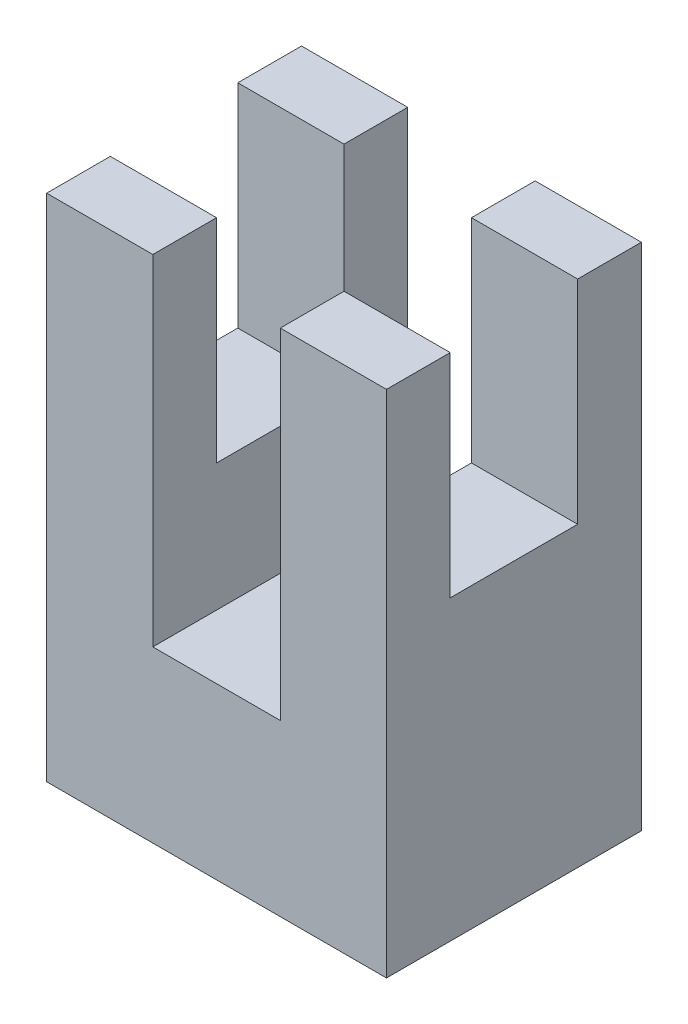
SolidWorks part; units mm, degrees
ref_plane "Alzado" through (0, 0, 0) normal (0, 0, 1) x (1, 0, 0)
ref_plane "Planta" through (0, 0, 0) normal (0, 1, 0) x (1, 0, 0)
ref_plane "Vista lateral" through (0, 0, 0) normal (1, 0, 0) x (0, 0, -1)
sketch "Croquis1" plane through (0, 0, 0) normal (0, 0, 1) x (1, 0, 0)
  line L0 (-20, 0) -> (20, 0)
  line L1 (20, 0) -> (20, 60)
  line L2 (20, 60) -> (7.5, 60)
  line L3 (7.5, 60) -> (7.5, 20)
  line L4 (7.5, 20) -> (-7.5, 20)
  line L5 (-7.5, 20) -> (-7.5, 60)
  line L6 (-7.5, 60) -> (-20, 60)
  line L7 (-20, 60) -> (-20, 0)
  point P11 (0, 0)
  dimension "D1" = 15
  dimension "D2" = 40
  dimension "D3" = 60
  dimension "D4" = 40
extrude "Saliente-Extruir1" add sketch "Croquis1" along normal mid plane 30
sketch "Croquis2" plane through (20, 0, 0) normal (1, 0, 0) x (0, 0, -1)
  line L0 (-7.5, 60) -> (-7.5, 35)
  line L1 (-15, 60) -> (15, 60) construction
  line L2 (-7.5, 35) -> (7.5, 35)
  line L3 (7.5, 35) -> (7.5, 60)
  line L4 (7.5, 60) -> (-7.5, 60)
  point P6 (0, 35)
  dimension "D1" = 15
  dimension "D2" = 25
extrude "Cortar-Extruir1" cut sketch "Croquis2" against normal up to next
mirror "Simetría1" about plane through (0, 0, 0) normal (1, 0, 0) of "Cortar-Extruir1"
